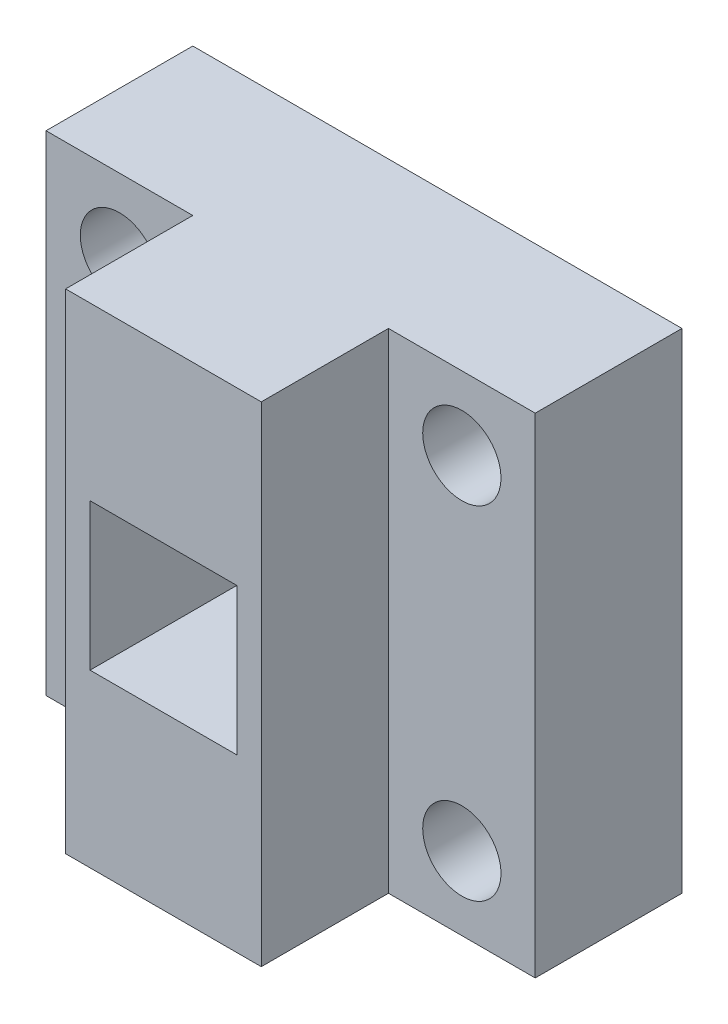
SolidWorks part; units mm, degrees
ref_plane "Спереди" through (0, 0, 0) normal (0, 0, 1) x (1, 0, 0)
ref_plane "Сверху" through (0, 0, 0) normal (0, 1, 0) x (1, 0, 0)
ref_plane "Справа" through (0, 0, 0) normal (1, 0, 0) x (0, 0, -1)
sketch "Эскиз1" plane through (0, 0, 0) normal (0, 0, 1) x (1, 0, 0)
  line L1 (-25, -25) -> (25, -25)
  line L2 (-25, -25) -> (-25, 25)
  line L3 (-25, 25) -> (25, 25)
  line L4 (25, -25) -> (25, 25)
  line L5 (-25, -25) -> (25, 25) construction
  line L6 (-25, 25) -> (25, -25) construction
  point P0 (0, 0)
  dimension "D1" = 50
extrude "Бобышка-Вытянуть1" add sketch "Эскиз1" along normal blind 15
sketch "Эскиз2" plane through (0, 0, 15) normal (0, 0, 1) x (1, 0, 0)
  line L0 (25, 25) -> (-25, 25) construction
  line L1 (-10, -25) -> (10, -25)
  line L2 (-10, -25) -> (-10, 25)
  line L3 (-10, 25) -> (10, 25)
  line L4 (10, -25) -> (10, 25)
  line L5 (-10, -25) -> (10, 25) construction
  line L6 (-10, 25) -> (10, -25) construction
  point P0 (0, 0)
  dimension "D1" = 20
extrude "Бобышка-Вытянуть2" add sketch "Эскиз2" along normal blind 13
sketch "Эскиз3" plane through (0, 0, 28) normal (0, 0, 1) x (1, 0, 0)
  line L1 (-7.5, -7.5) -> (7.5, -7.5)
  line L2 (-7.5, -7.5) -> (-7.5, 7.5)
  line L3 (-7.5, 7.5) -> (7.5, 7.5)
  line L4 (7.5, -7.5) -> (7.5, 7.5)
  line L5 (-7.5, -7.5) -> (7.5, 7.5) construction
  line L6 (-7.5, 7.5) -> (7.5, -7.5) construction
  point P0 (0, 0)
  dimension "D1" = 15
extrude "Вырез-Вытянуть1" cut sketch "Эскиз3" against normal through all
sketch "Эскиз5" plane through (0, 0, 0) normal (0, 0, -1) x (-1, 0, 0)
  line L0 (25, -25) -> (-25, -25) construction
  line L1 (-25, -25) -> (-25, 25) construction
  circle A0 centre (-17.5, -17.5) radius 4
  dimension "D1" = 8
  dimension "D2" = 7.5
  dimension "D3" = 7.5
extrude "Вырез-Вытянуть3" cut sketch "Эскиз5" against normal through all
mirror "Зеркальное отражение1" about plane through (0, 0, 0) normal (0, 1, 0) of "Вырез-Вытянуть3"
mirror "Зеркальное отражение2" about plane through (0, 0, 0) normal (1, 0, 0) of "Зеркальное отражение1", "Вырез-Вытянуть3"
